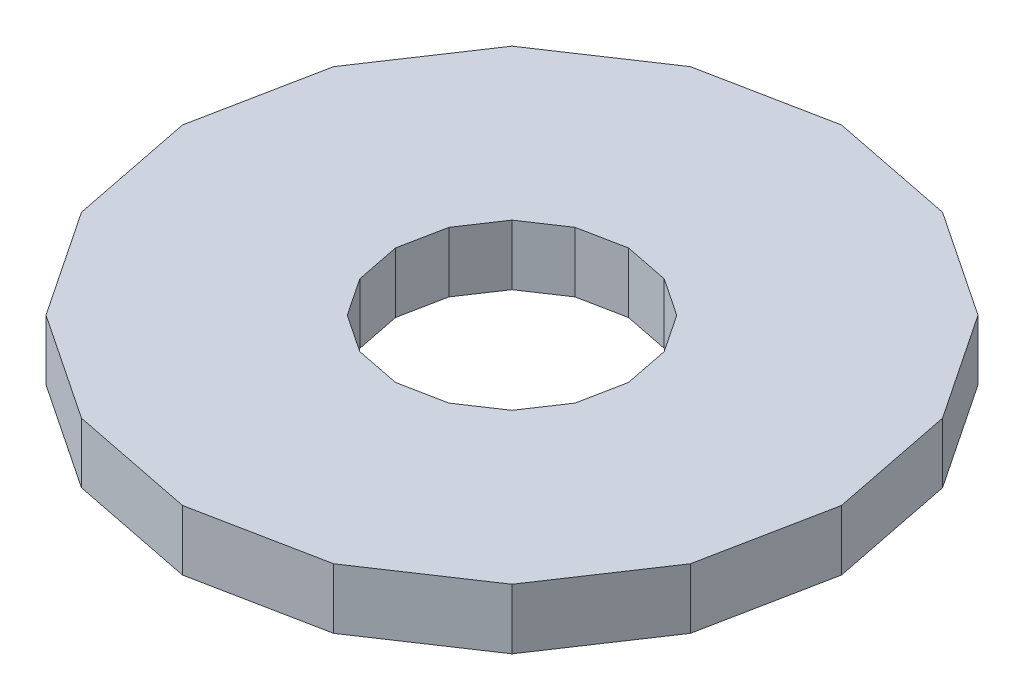
SolidWorks part; units mm, degrees
ref_plane "Front Plane" through (0, 0, 0) normal (0, 0, 1) x (1, 0, 0)
ref_plane "Top Plane" through (0, 0, 0) normal (0, 1, 0) x (1, 0, 0)
ref_plane "Right Plane" through (0, 0, 0) normal (1, 0, 0) x (0, 0, -1)
sketch "Sketch1" plane through (0, 0, 0) normal (0, 1, 0) x (1, 0, 0)
  line L1 (36.8231, 0) -> (34.0201, 14.0916)
  line L2 (34.0201, 14.0916) -> (26.0379, 26.0379)
  line L3 (26.0379, 26.0379) -> (14.0916, 34.0201)
  line L4 (14.0916, 34.0201) -> (0, 36.8231)
  line L5 (0, 36.8231) -> (-14.0916, 34.0201)
  line L6 (-14.0916, 34.0201) -> (-26.0379, 26.0379)
  line L7 (-26.0379, 26.0379) -> (-34.0201, 14.0916)
  line L8 (-34.0201, 14.0916) -> (-36.8231, 0)
  line L9 (-36.8231, 0) -> (-34.0201, -14.0916)
  line L10 (-34.0201, -14.0916) -> (-26.0379, -26.0379)
  line L11 (-26.0379, -26.0379) -> (-14.0916, -34.0201)
  line L12 (-14.0916, -34.0201) -> (0, -36.8231)
  line L13 (0, -36.8231) -> (14.0916, -34.0201)
  line L14 (14.0916, -34.0201) -> (26.0379, -26.0379)
  line L15 (26.0379, -26.0379) -> (34.0201, -14.0916)
  line L16 (34.0201, -14.0916) -> (36.8231, 0)
  line L17 (104.1569, 0) -> (96.2284, 39.8591)
  line L18 (96.2284, 39.8591) -> (73.65, 73.65)
  line L19 (73.65, 73.65) -> (39.8591, 96.2284)
  line L20 (39.8591, 96.2284) -> (0, 104.1569)
  line L21 (0, 104.1569) -> (-39.8591, 96.2284)
  line L22 (-39.8591, 96.2284) -> (-73.65, 73.65)
  line L23 (-73.65, 73.65) -> (-96.2284, 39.8591)
  line L24 (-96.2284, 39.8591) -> (-104.1569, 0)
  line L25 (-104.1569, 0) -> (-96.2284, -39.8591)
  line L26 (-96.2284, -39.8591) -> (-73.65, -73.65)
  line L27 (-73.65, -73.65) -> (-39.8591, -96.2284)
  line L28 (-39.8591, -96.2284) -> (0, -104.1569)
  line L29 (0, -104.1569) -> (39.8591, -96.2284)
  line L30 (39.8591, -96.2284) -> (73.65, -73.65)
  line L31 (73.65, -73.65) -> (96.2284, -39.8591)
  line L32 (96.2284, -39.8591) -> (104.1569, 0)
  circle A0 centre (0, 0) radius 36.1155 construction
  circle A1 centre (0, 0) radius 102.1555 construction
  dimension "D1" = 40.64
  dimension "D2" = 66.04
extrude "Boss-Extrude1" add sketch "Sketch1" along normal blind 19.05
